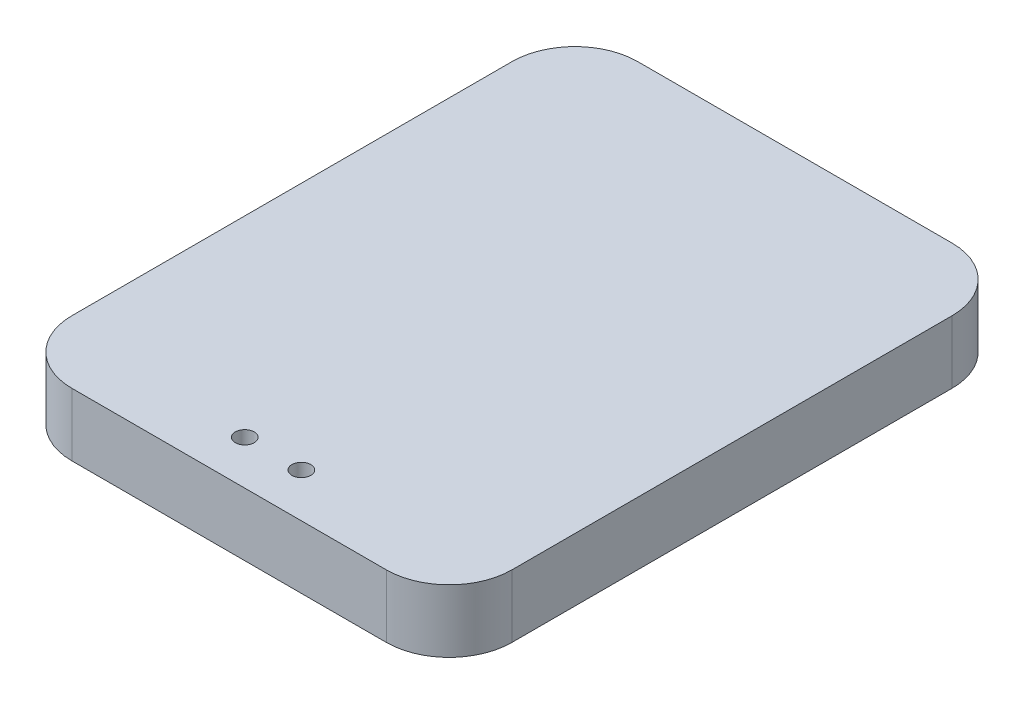
SolidWorks part; units mm, degrees
ref_plane "Front Plane" through (0, 0, 0) normal (0, 0, 1) x (1, 0, 0)
ref_plane "Top Plane" through (0, 0, 0) normal (0, 1, 0) x (1, 0, 0)
ref_plane "Right Plane" through (0, 0, 0) normal (1, 0, 0) x (0, 0, -1)
sketch "Sketch1" plane through (0, 0, 0) normal (0, 1, 0) x (1, 0, 0)
  line L1 (35, -45) -> (-35, -45)
  line L2 (35, -45) -> (35, 45)
  line L3 (35, 45) -> (-35, 45)
  line L4 (-35, -45) -> (-35, 45)
  line L5 (35, -45) -> (-35, 45) construction
  line L6 (35, 45) -> (-35, -45) construction
  point P0 (0, 0)
  dimension "D1" = 90
  dimension "D2" = 70
extrude "Boss-Extrude1" add sketch "Sketch1" along normal mid plane 10
fillet "Fillet1" radius 10 4 edges at (-35, 0, -45) (35, 0, -45) (35, 0, 45) (-35, 0, 45)
sketch "Sketch2" plane through (0, 5, 0) normal (0, 1, 0) x (1, 0, 0)
  circle A0 centre (-4.5, -38) radius 1.5
  circle A1 centre (4.5, -38) radius 1.5
extrude "Cut-Extrude1" cut sketch "Sketch2" against normal blind 10
